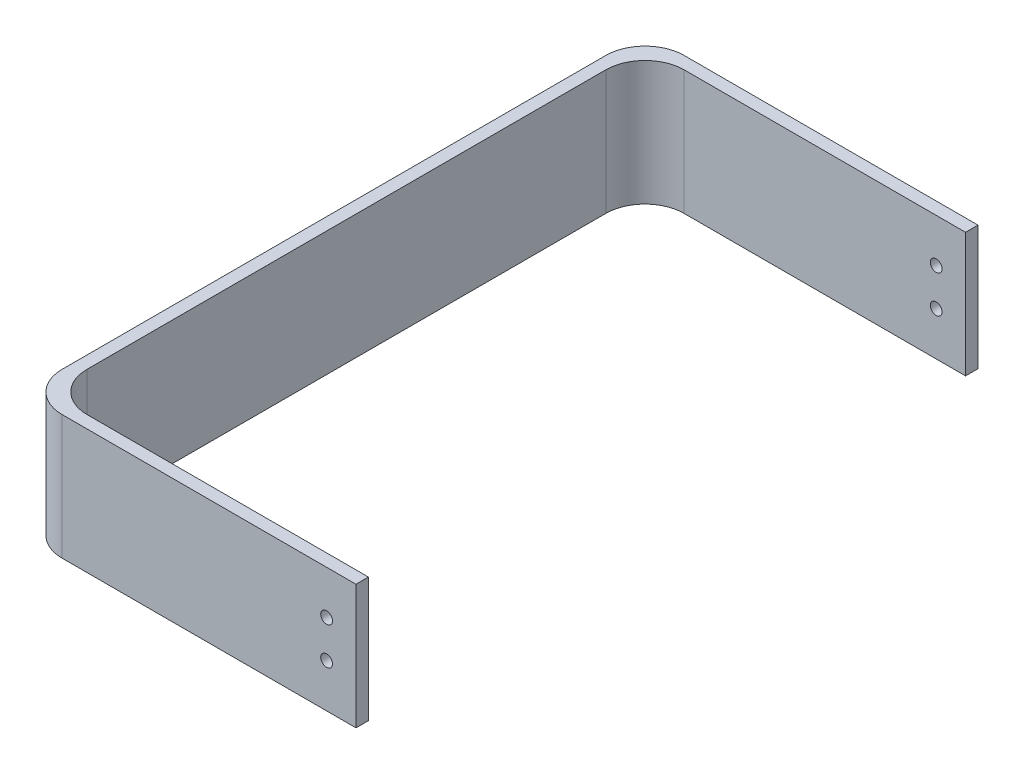
SolidWorks part; units mm, degrees
ref_plane "Front Plane" through (0, 0, 0) normal (0, 0, 1) x (1, 0, 0)
ref_plane "Top Plane" through (0, 0, 0) normal (0, 1, 0) x (1, 0, 0)
ref_plane "Right Plane" through (0, 0, 0) normal (1, 0, 0) x (0, 0, -1)
sketch "Sketch1" plane through (0, 0, 0) normal (0, 1, 0) x (1, 0, 0)
  line L0 (0, 0) -> (-85, 0)
  line L1 (-85, 0) -> (-85, 158.75)
  line L2 (-85, 158.75) -> (0, 158.75)
  line L3 (0, 3.175) -> (-81.825, 3.175)
  line L4 (-81.825, 3.175) -> (-81.825, 155.575)
  line L5 (-81.825, 155.575) -> (0, 155.575)
  line L6 (0, 158.75) -> (0, 155.575)
  line L7 (0, 3.175) -> (0, 0)
  dimension "D1" = 85
  dimension "D2" = 158.75
  dimension "D3" = 0
  dimension "D4" = 3.175
extrude "Boss-Extrude1" add sketch "Sketch1" along normal blind 31.75
sketch "Sketch2" plane through (0, 0, 0) normal (0, 0, 1) x (1, 0, 0)
  line L2 (-85, 31.75) -> (0, 31.75) construction
  line L3 (-85, 0) -> (0, 0) construction
  line L4 (0, 31.75) -> (0, 0) construction
  circle A0 centre (-7.5, 20.6375) radius 1.5
  circle A1 centre (-7.5, 11.1125) radius 1.5
  point P0 (-7.5, 20.6375)
  point P1 (-7.5, 11.1125)
  dimension "D5" = 3
  dimension "D6" = 3
  dimension "D1" = 9.525
  dimension "D2" = 11.1125
  dimension "D3" = 11.1125
  dimension "D4" = 7.5
extrude "Cut-Extrude1" cut sketch "Sketch2" against normal through all contours A1 | A0
fillet "Fillet1" radius 10 4 edges at (-81.825, 15.875, -3.175) (-81.825, 15.875, -155.575) (-85, 15.875, -158.75) (-85, 15.875, 0)
